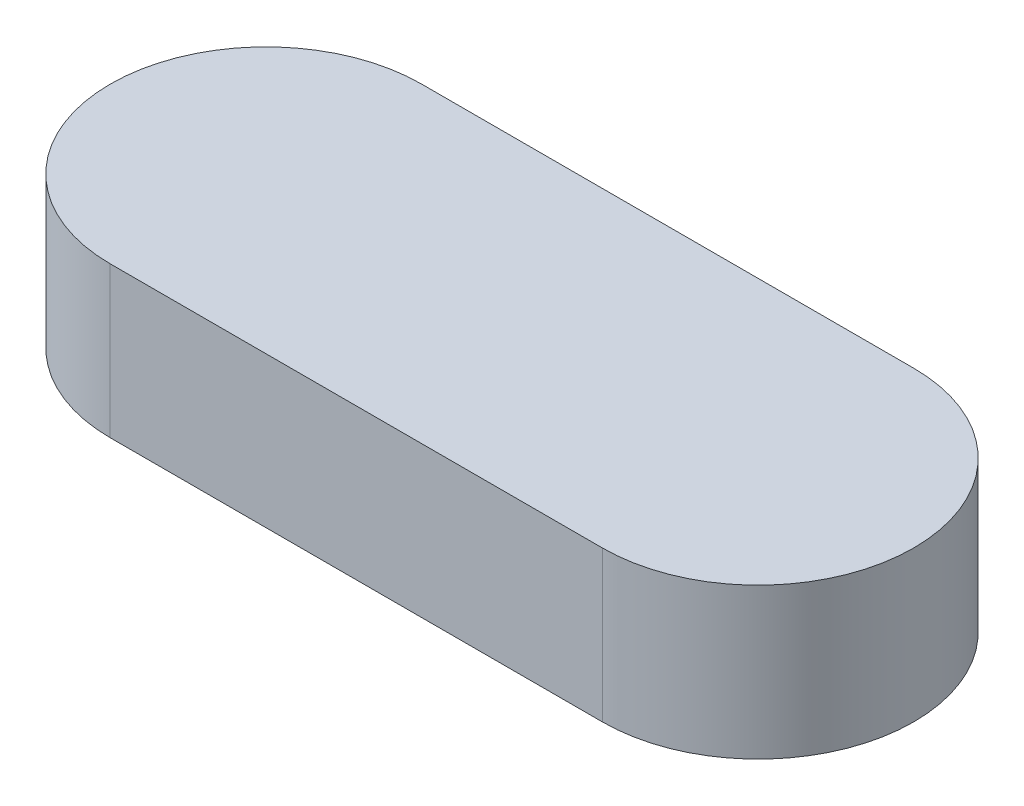
SolidWorks part; units mm, degrees
ref_plane "Front Plane" through (0, 0, 0) normal (0, 0, 1) x (1, 0, 0)
ref_plane "Top Plane" through (0, 0, 0) normal (0, 1, 0) x (1, 0, 0)
ref_plane "Right Plane" through (0, 0, 0) normal (1, 0, 0) x (0, 0, -1)
sketch "Sketch2" plane through (0, 0, 0) normal (0, 1, 0) x (1, 0, 0)
  line L0 (-12.25, 0) -> (12.25, 0) construction
  line L1 (-12.25, 7.75) -> (12.25, 7.75)
  line L2 (-12.25, -7.75) -> (12.25, -7.75)
  arc A0 (-12.25, 7.75) -> (-12.25, -7.75) centre (-12.25, 0) ccw
  arc A1 (12.25, -7.75) -> (12.25, 7.75) centre (12.25, 0) ccw
  point P3 (0, 0)
  point P8 (0, 0)
  dimension "D2" = 7.75
  dimension "D1" = 24.5
extrude "Boss-Extrude1" add sketch "Sketch2" along normal blind 7.5
